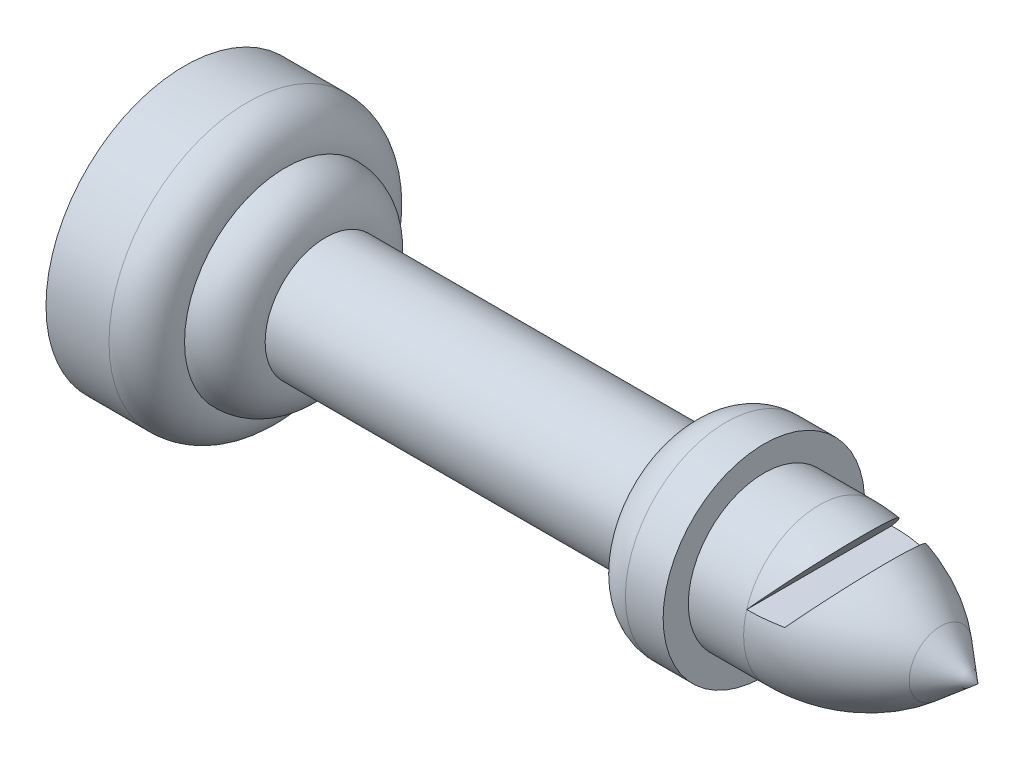
SolidWorks part; units mm, degrees
ref_plane "Спереди" through (0, 0, 0) normal (0, 0, 1) x (1, 0, 0)
ref_plane "Сверху" through (0, 0, 0) normal (0, 1, 0) x (1, 0, 0)
ref_plane "Справа" through (0, 0, 0) normal (1, 0, 0) x (0, 0, -1)
other "Configuration Table"
sketch "Эскиз1" plane through (0, 0, 0) normal (0, 0, 1) x (1, 0, 0)
  line L0 (0, 11) -> (63, 11) construction
  line L1 (0, 0) -> (5, 0)
  line L2 (0, 0) -> (0, 22)
  line L3 (0, 22) -> (5, 22)
  line L4 (5, 0) -> (5, 22)
  line L5 (5, 19) -> (8, 19)
  line L6 (5, 19) -> (5, 3)
  line L7 (5, 3) -> (8, 3)
  line L8 (8, 19) -> (8, 3)
  line L9 (8, 15.8) -> (43, 15.8)
  line L10 (8, 15.8) -> (8, 6.2)
  line L11 (8, 6.2) -> (43, 6.2)
  line L12 (43, 15.8) -> (43, 6.2)
  line L13 (43, 3) -> (46, 3)
  line L14 (43, 3) -> (43, 19)
  line L15 (43, 19) -> (46, 19)
  line L16 (46, 3) -> (46, 19)
  line L18 (46, 13.3632) -> (46, 9)
  line L19 (46, 5) -> (50.3899, 5)
  line L20 (60.0317, 8.5093) -> (63, 11)
  arc A0 (5, 0) -> (8, 3) centre (5, 3) ccw
  arc A1 (8, 3) -> (11.2, 6.2) centre (8, 6.2) ccw
  arc A2 (43, 3) -> (39.8, 6.2) centre (43, 6.2) cw
  arc A3 (50.3899, 5) -> (60.0317, 8.5093) centre (50.3899, 20) ccw
  point P28 (44.5, 3)
  dimension "D8" = 3
  dimension "D9" = 3.2
  dimension "D15" = 3.2
  dimension "D19" = 2
  dimension "D16" = 15
  dimension "D12" = 3
  dimension "D14" = 4.3632
  dimension "D1" = 22
  dimension "D2" = 5
  dimension "D3" = 3
  dimension "D4" = 3
  dimension "D5" = 3
  dimension "D6" = 3.2
  dimension "D7" = 3.2
  dimension "D10" = 35
  dimension "D11" = 3.2
  dimension "D13" = 16
  dimension "D17" = 17
  dimension "D18" = 6
  dimension "D20" = 140
revolve "Повернуть1" add sketch "Эскиз1" angle 360 about L0
sketch "Эскиз2" plane through (0, 0, 0) normal (0, 0, 1) x (1, 0, 0)
  line L0 (50.3899, 12.6886) -> (54.1677, 17)
  line L1 (50.3899, 17) -> (50.3899, 5) construction
  line L2 (54.1677, 17) -> (55.9994, 15.9514)
  line L3 (55.9994, 15.9514) -> (53.1405, 12.6886)
  line L4 (50.3899, 12.6886) -> (53.1405, 12.6886)
  line L5 (46, 3) -> (46, 19) construction
  line L8 (46, 5) -> (46, 17) construction
  line L9 (60.0317, 13.4907) -> (60.0317, 8.5093) construction
  dimension "D1" = 4.3899
  dimension "D2" = 2.7506
  dimension "D3" = 2.1106
  dimension "D4" = 4.3381
  dimension "D5" = 5.7323
  dimension "D6" = 131.226
  dimension "D7" = 78.563
  dimension "D8" = 119.789
  dimension "D9" = 4.3899
  dimension "D10" = 7.1405
  dimension "D11" = 9.6418
extrude "Вырез-Вытянуть1" cut sketch "Эскиз2" against normal blind 10 contours L0 L2 L3 L4
sketch "Эскиз3" plane through (0, 0, 0) normal (0, 1, 0) x (1, 0, 0)
  line L0 (0, 0) -> (75.7107, 0) construction
mirror "Зеркальное отражение1" about plane through (0, 0, 0) normal (0, 0, 1) of "Вырез-Вытянуть1"
sketch "Эскиз5" plane through (0, 0, 0) normal (-1, 0, 0) x (0, 0, 1)
  line L0 (-7.9528, 3.4004) -> (7.9528, 18.5996) construction
  line L1 (-6.6516, 19.761) -> (6.6516, 2.239) construction
  circle A0 centre (0, 11) radius 11 construction
  circle A1 centre (0, 11) radius 10
  dimension "D1" = 20
extrude "Вырез-Вытянуть2" cut sketch "Эскиз5" against normal blind 2.5
